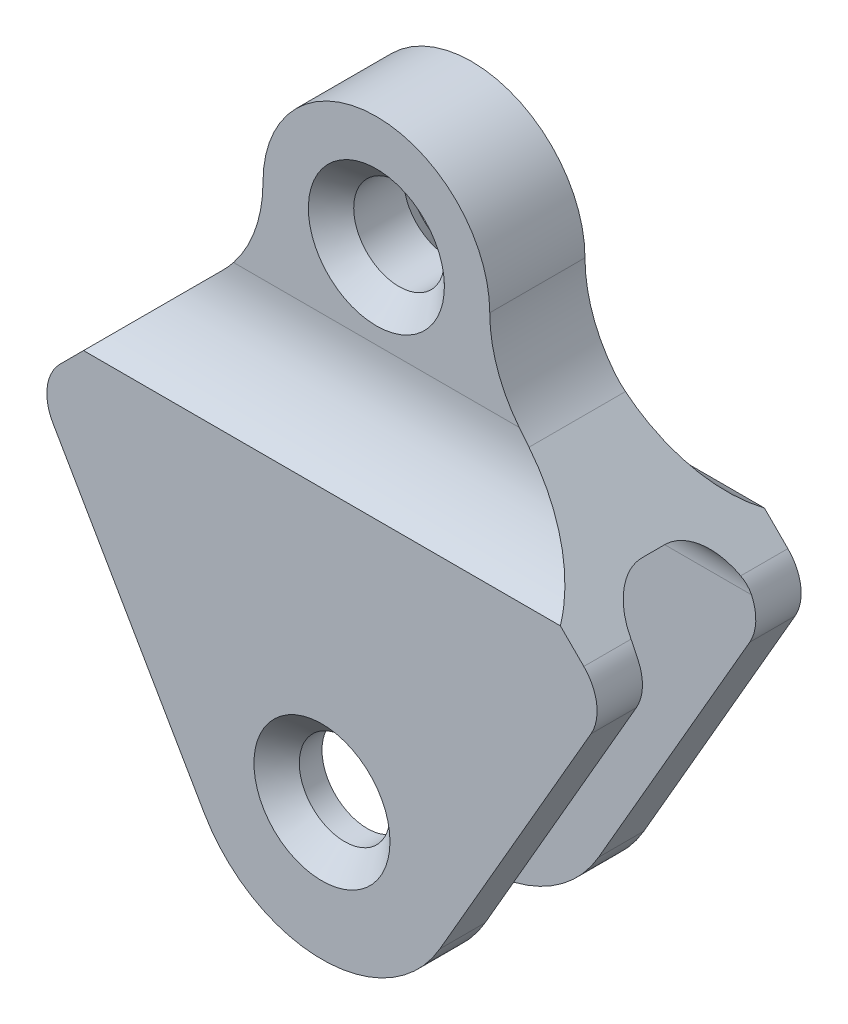
SolidWorks part; units mm, degrees
material "Titanium Ti-8Mn, Annealed"
ref_plane "Front Plane" through (0, 0, 0) normal (0, 0, 1) x (1, 0, 0)
ref_plane "Top Plane" through (0, 0, 0) normal (0, 1, 0) x (1, 0, 0)
ref_plane "Right Plane" through (0, 0, 0) normal (1, 0, 0) x (0, 0, -1)
sketch "Sketch1" plane through (0, 0, 0) normal (0, 0, 1) x (1, 0, 0)
  line L0 (-57.7405, 54.8331) -> (-33.7868, 78.7868)
  line L1 (-59.3297, 42.762) -> (-25.9808, -15)
  line L2 (0, 0) -> (0, 100) construction
  line L3 (59.3297, 42.762) -> (25.9808, -15)
  line L4 (57.7405, 54.8331) -> (33.7868, 78.7868)
  circle A0 centre (0, 100) radius 10
  circle A1 centre (0, 0) radius 10
  arc A2 (25, 100) -> (-25, 100) centre (0, 100) ccw
  arc A3 (-25.9808, -15) -> (25.9808, -15) centre (0, 0) ccw
  arc A4 (-33.7868, 78.7868) -> (-25, 100) centre (-55, 100) ccw
  arc A5 (-57.7405, 54.8331) -> (-59.3297, 42.762) centre (-50.6694, 47.762) ccw
  arc A6 (57.7405, 54.8331) -> (59.3297, 42.762) centre (50.6694, 47.762) cw
  arc A7 (33.7868, 78.7868) -> (25, 100) centre (55, 100) cw
  dimension "D1" = 20
  dimension "D2" = 50
  dimension "D3" = 20
  dimension "D4" = 20
  dimension "D7" = 10
  dimension "D9" = 30
  dimension "D5" = 100
  dimension "D6" = 30
  dimension "D8" = 45
extrude "Boss-Extrude1" add sketch "Sketch1" along normal mid plane 45
sketch "Sketch2" plane through (0, 0, 0) normal (1, 0, 0) x (0, 0, -1)
  line L0 (-10.5, 125) -> (-10.5, 81.3542)
  line L1 (22.5, 125) -> (-22.5, 125) construction
  line L2 (-22.5, 54.8331) -> (-22.5, 78.7868) construction
  line L3 (-22.5, 60) -> (-22.5, 125)
  line L4 (-22.5, 125) -> (-10.5, 125)
  line L9 (-22.5, -30) -> (22.5, -30) construction
  line L14 (-2.5, 62) -> (2.5, 62)
  line L15 (-12.5, 52) -> (-12.5, -30)
  line L16 (-12.5, -30) -> (12.5, -30)
  line L17 (12.5, 52) -> (12.5, -30)
  line L18 (-12.5, 62) -> (12.5, -30) construction
  line L19 (-12.5, -30) -> (12.5, 62) construction
  line L20 (0, 0) -> (0, 125) construction
  line L21 (22.5, 60) -> (22.5, 125)
  line L22 (22.5, 125) -> (10.5, 125)
  line L23 (10.5, 125) -> (10.5, 81.3542)
  arc A0 (-10.5, 81.3542) -> (-22.5, 60) centre (-35.5, 81.3542) cw
  arc A3 (2.5, 62) -> (12.5, 52) centre (2.5, 52) cw
  arc A4 (-2.5, 62) -> (-12.5, 52) centre (-2.5, 52) ccw
  arc A5 (10.5, 81.3542) -> (22.5, 60) centre (35.5, 81.3542) ccw
  point P9 (0, 16)
  point P17 (9.4679, 125)
  dimension "D2" = 25
  dimension "D5" = 25
  dimension "D6" = 10
  dimension "D1" = 12
  dimension "D3" = 65
  dimension "D4" = 92
extrude "Cut-Extrude1" cut sketch "Sketch2" against normal through all both and the other way through all contours A0 L0 L4 L3 | L15 A4 L14 A3 L17 L16 | L21 L22 L23 A5
chamfer "Chamfer1" distance 5 angle 45 4 edges at (10, 0, -22.5) (10, 0, 22.5) (0, 90, -10.5) (0, 90, 10.5)
